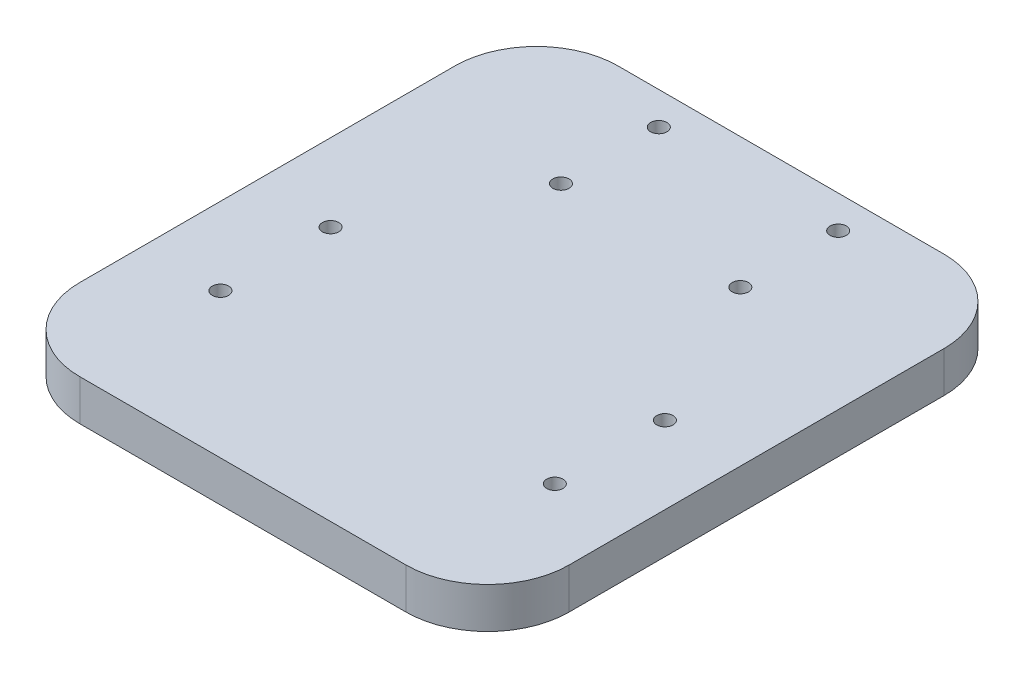
SolidWorks part; units mm, degrees
ref_plane "Front Plane" through (0, 0, 0) normal (0, 0, 1) x (1, 0, 0)
ref_plane "Top Plane" through (0, 0, 0) normal (0, 1, 0) x (1, 0, 0)
ref_plane "Right Plane" through (0, 0, 0) normal (1, 0, 0) x (0, 0, -1)
sketch "Sketch1" plane through (0, -23, 0) normal (0, -1, 0) x (1, 0, 0)
  line L0 (-9, 28) -> (9, 28) construction
  line L1 (-30, 28) -> (30, 28)
  line L2 (-30, 28) -> (-30, -38)
  line L3 (-30, -38) -> (30, -38)
  line L4 (30, 28) -> (30, -38)
  line L5 (-11, -38) -> (11, -38) construction
  point P6 (0, -38)
  dimension "D1" = 60
extrude "Boss-Extrude1" add sketch "Sketch1" along normal blind 5
fillet "Fillet1" radius 10 4 edges at (30, -25.5, -38) (30, -25.5, 28) (-30, -25.5, -38) (-30, -25.5, 28)
shell "Shell1" thickness 2
fillet "Fillet2" radius 2 8 edges at (25.6569, -25, -33.6569) (0, -25, -36) (-25.6569, -25, -33.6569) (-28, -25, -5) (-25.6569, -25, 23.6569) (0, -25, 26) (25.6569, -25, 23.6569) (28, -25, -5)
sketch "Sketch3" plane through (0, -23, 0) normal (0, 1, 0) x (1, 0, 0)
  circle A0 centre (20.5, 3.25) radius 1 construction
  circle A1 centre (20.5, -10.25) radius 1 construction
  circle A2 centre (11, 34) radius 1 construction
  circle A3 centre (11, 22) radius 1 construction
  circle A4 centre (-11, 34) radius 1 construction
  circle A5 centre (-11, 22) radius 1 construction
  circle A6 centre (-20.5, 3.25) radius 1 construction
  circle A7 centre (-20.5, -10.25) radius 1 construction
  circle A8 centre (20.5, 3.25) radius 1
  circle A9 centre (20.5, -10.25) radius 1
  circle A10 centre (11, 34) radius 1
  circle A11 centre (11, 22) radius 1
  circle A12 centre (-11, 34) radius 1
  circle A13 centre (-11, 22) radius 1
  circle A14 centre (-20.5, 3.25) radius 1
  circle A15 centre (-20.5, -10.25) radius 1
extrude "Cut-Extrude1" cut sketch "Sketch3" against normal blind 5
